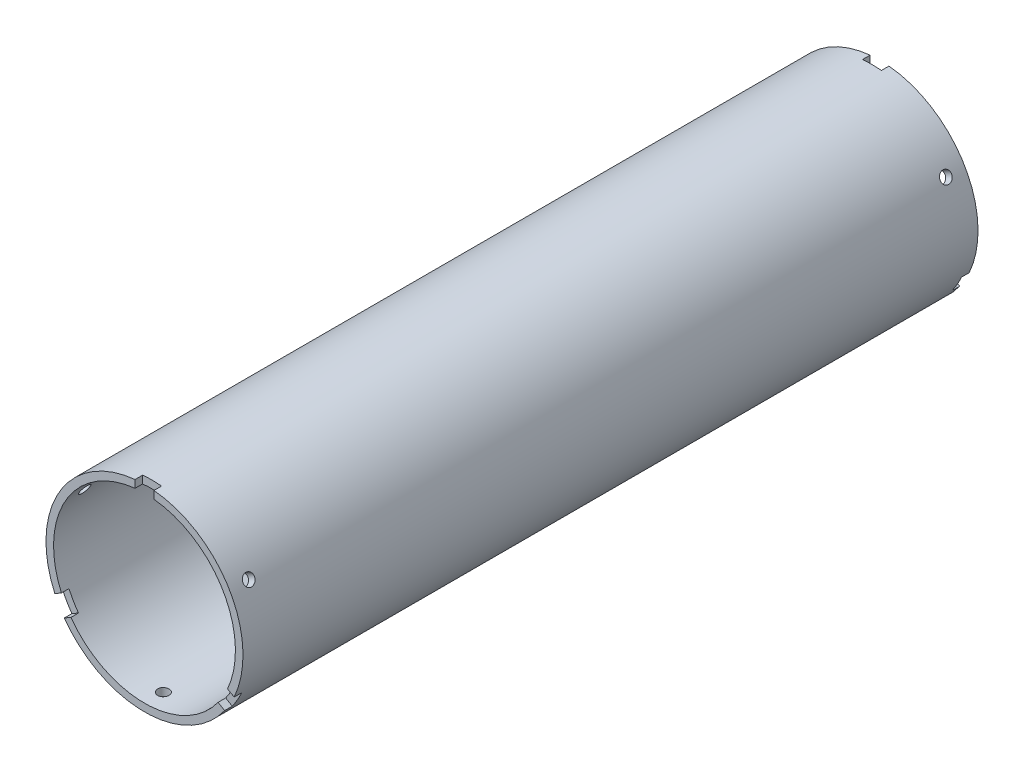
SolidWorks part; units mm, degrees
material "1060 Сплав"
ref_plane "Спереди" through (0, 0, 0) normal (0, 0, 1) x (1, 0, 0)
ref_plane "Сверху" through (0, 0, 0) normal (0, 1, 0) x (1, 0, 0)
ref_plane "Справа" through (0, 0, 0) normal (1, 0, 0) x (0, 0, -1)
sketch "Эскиз1" plane through (0, 0, 0) normal (0, 0, 1) x (1, 0, 0)
  circle A0 centre (0, 0) radius 26
  circle A1 centre (0, 0) radius 24
  dimension "D1" = 52
  dimension "D2" = 2
extrude "Бобышка-Вытянуть1" add sketch "Эскиз1" along normal blind 194
sketch "Эскиз2" plane through (0, 0, 0) normal (0, 1, 0) x (1, 0, 0)
  line L0 (0, 0) -> (0, -194) construction
  line L1 (24, 0) -> (-24, 0) construction
  line L2 (-26, -194) -> (26, -194) construction
  line L3 (26, 0) -> (-26, 0) construction
  circle A0 centre (0, -5) radius 1.5
  circle A1 centre (0, -189) radius 1.5
  dimension "D1" = 3
  dimension "D4" = 3
  dimension "D2" = 5
  dimension "D3" = 5
extrude "Вырез-Вытянуть1" cut sketch "Эскиз2" against normal blind 88
pattern_circular "Круговой массив1" count 3 over 360 about axis through (0, 0, 194) along (0, 0, -1) of "Вырез-Вытянуть1"
sketch "Эскиз3" plane through (0, 0, 0) normal (0, 0, -1) x (-1, 0, 0)
  line L0 (0, 0) -> (0, 38.5898) construction
  line L2 (-2.5, 28.6079) -> (2.5, 28.6079)
  line L3 (-2.5, 28.6079) -> (-2.5, 17.134)
  line L4 (-2.5, 17.134) -> (2.5, 17.134)
  line L5 (2.5, 28.6079) -> (2.5, 17.134)
  line L6 (-2.5, 28.6079) -> (2.5, 17.134) construction
  line L7 (-2.5, 17.134) -> (2.5, 28.6079) construction
  point P4 (0, 22.8709)
  dimension "D1" = 5
extrude "Вырез-Вытянуть2" cut sketch "Эскиз3" against normal blind 2
pattern_circular "Круговой массив2" count 3 over 360 about axis through (0, 0, 0) along (0, 0, 1) of "Вырез-Вытянуть2"
sketch "Эскиз4" plane through (0, 0, 194) normal (0, 0, 1) x (1, 0, 0)
  line L4 (2.5, 28.6079) -> (-2.5, 28.6079)
  line L5 (-2.5, 28.6079) -> (-2.5, 17.134)
  line L6 (-2.5, 17.134) -> (2.5, 17.134)
  line L7 (2.5, 17.134) -> (2.5, 28.6079)
  line L8 (2.5, 28.6079) -> (-2.5, 28.6079)
  line L9 (-2.5, 28.6079) -> (-2.5, 17.134)
  line L10 (-2.5, 17.134) -> (2.5, 17.134)
  line L11 (2.5, 17.134) -> (2.5, 28.6079)
  dimension "D1" = 0
extrude "Вырез-Вытянуть3" cut sketch "Эскиз4" against normal blind 2
pattern_circular "Круговой массив3" count 3 over 360 about axis through (0, 0, 0) along (0, 0, 1) of "Вырез-Вытянуть3"
